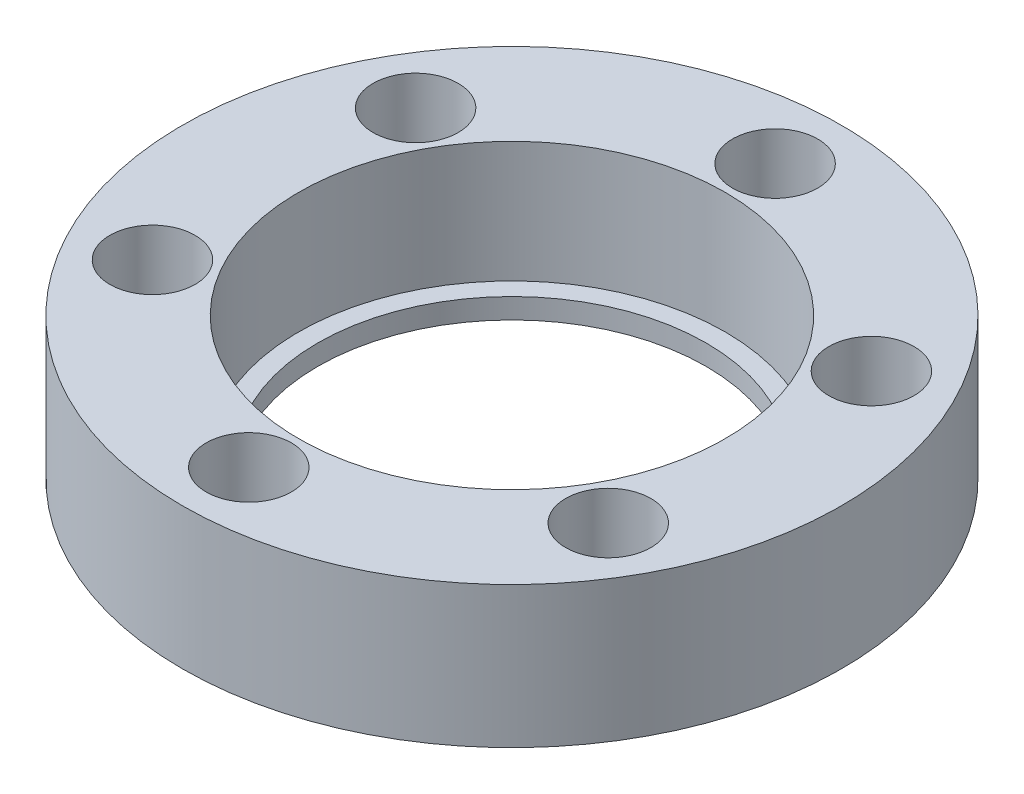
SolidWorks part; units mm, degrees
ref_plane "Front Plane" through (0, 0, 0) normal (0, 0, 1) x (1, 0, 0)
ref_plane "Top Plane" through (0, 0, 0) normal (0, 1, 0) x (1, 0, 0)
ref_plane "Right Plane" through (0, 0, 0) normal (1, 0, 0) x (0, 0, -1)
sketch "Sketch1" plane through (0, 0, 0) normal (0, 1, 0) x (1, 0, 0)
  circle A0 centre (0, 0) radius 16.891
  dimension "D1" = 33.782
extrude "Extrude1" add sketch "Sketch1" along normal blind 7.239
sketch "Sketch2" plane through (0, 0, 0) normal (0, -1, 0) x (1, 0, 0)
  circle A0 centre (0, 0) radius 10.9347
  circle A1 centre (0, 0) radius 16.891 construction
  dimension "D1" = 5.9563
extrude "Extrude2" cut sketch "Sketch2" against normal through all
sketch "Sketch3" plane through (0, 0, 0) normal (0, -1, 0) x (1, 0, 0)
  circle A0 centre (0, 0) radius 9.9568
  circle A1 centre (0, 0) radius 10.9347
  circle A2 centre (0, 0) radius 16.891 construction
  circle A3 centre (0, 0) radius 10.9347 construction
  dimension "D1" = 6.9342
extrude "Extrude3" add sketch "Sketch3" against normal blind 1.0414
sketch "Sketch4" plane through (0, 7.239, 0) normal (0, 1, 0) x (1, 0, 0)
  circle A0 centre (0, 13.4874) radius 2.1844
  dimension "D1" = 4.3688
  dimension "D2" = 13.4874
extrude "Extrude4" cut sketch "Sketch4" against normal through all
pattern_circular "CirPattern1" count 6 over 360 about axis through (0, 0, 0) along (0, 1, 0) of "Extrude4"
